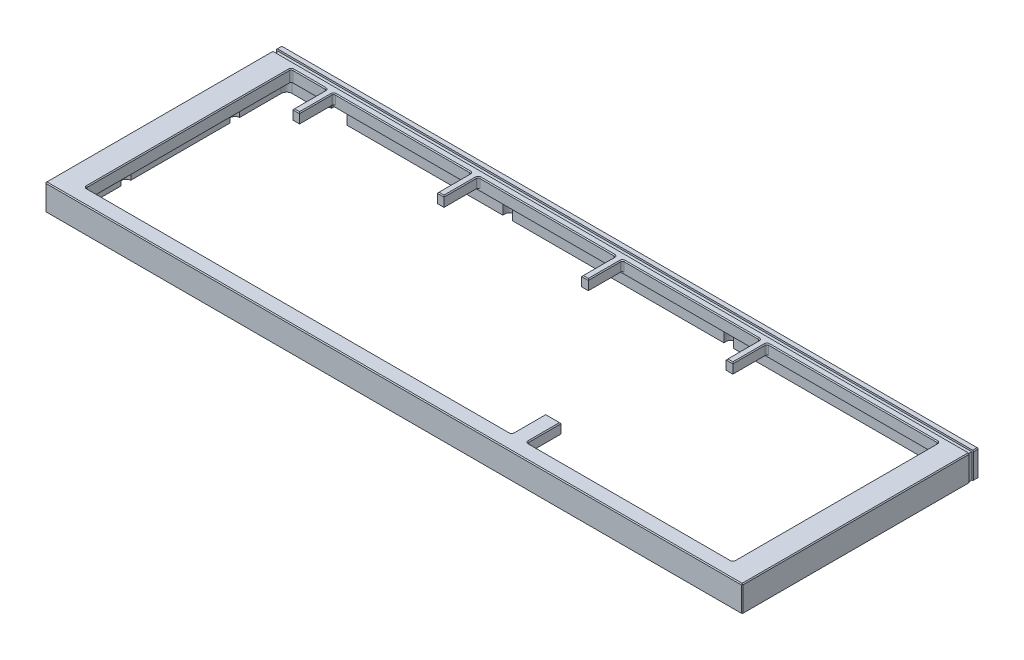
SolidWorks part; units mm, degrees
material "6061-T6 (SS)"
ref_plane "Front Plane" through (0, 0, 0) normal (0, 0, 1) x (1, 0, 0)
ref_plane "Top Plane" through (0, 0, 0) normal (0, 1, 0) x (1, 0, 0)
ref_plane "Right Plane" through (0, 0, 0) normal (1, 0, 0) x (0, 0, -1)
sketch "Sketch1" plane through (0, 0, 0) normal (0, 1, 0) x (1, 0, 0)
  line L1 (0, 0) -> (390.74, 0)
  line L2 (0, 0) -> (0, 132.7)
  line L3 (0, 132.7) -> (390.74, 132.7)
  line L4 (390.74, 0) -> (390.74, 132.7)
  line L5 (13.92, 124) -> (376.82, 124)
  line L6 (13.92, 124) -> (13.92, 8.7)
  line L7 (13.92, 8.7) -> (376.82, 8.7)
  line L8 (376.82, 124) -> (376.82, 8.7)
  point P9 (195.37, 124)
  point P10 (195.37, 132.7)
  point P11 (13.92, 66.35)
  point P12 (0, 66.35)
  dimension "D1" = 362.9
  dimension "D2" = 115.3
  dimension "D3" = 8.7
  dimension "D4" = 13.92
extrude "Main Body" add sketch "Sketch1" along normal blind 14.8
sketch "Sketch2" plane through (0, 0, 0) normal (0, -1, 0) x (1, 0, 0)
  line L0 (390.74, -132.7) -> (0, -132.7) construction
  line L1 (388.74, -130.7) -> (2, -130.7)
  line L2 (388.74, -130.7) -> (388.74, -2)
  line L3 (388.74, -2) -> (2, -2)
  line L4 (2, -130.7) -> (2, -2)
  line L5 (390.74, 0) -> (390.74, -132.7) construction
  point P4 (195.37, -130.7)
  point P7 (195.37, -132.7)
  point P8 (388.74, -66.35)
  point P11 (390.74, -66.35)
  dimension "D1" = 2
  dimension "D2" = 2
extrude "Alignment Guide" cut sketch "Sketch2" against normal blind 1 contours L2 L1 L4 L3
sketch "Sketch3" plane through (0, 14.8, 0) normal (0, 1, 0) x (1, 0, 0)
  line L0 (13.92, 8.7) -> (376.82, 8.7) construction
  line L1 (252.82, 27.8) -> (261.52, 27.8)
  line L2 (252.82, 27.8) -> (252.82, 8.7)
  line L3 (252.82, 8.7) -> (261.52, 8.7)
  line L4 (261.52, 27.8) -> (261.52, 8.7)
  line L5 (376.82, 8.7) -> (376.82, 124) construction
  line L6 (376.82, 124) -> (13.92, 124) construction
  line L7 (33.92, 124) -> (37.72, 124)
  line L8 (33.92, 124) -> (33.92, 104.9)
  line L9 (33.92, 104.9) -> (37.72, 104.9)
  line L10 (37.72, 124) -> (37.72, 104.9)
  line L11 (13.92, 124) -> (13.92, 8.7) construction
  line L12 (114.92, 124) -> (118.72, 124)
  line L13 (114.92, 124) -> (114.92, 104.9)
  line L14 (114.92, 104.9) -> (118.72, 104.9)
  line L15 (118.72, 124) -> (118.72, 104.9)
  line L16 (195.82, 124) -> (199.62, 124)
  line L17 (195.82, 124) -> (195.82, 104.9)
  line L18 (195.82, 104.9) -> (199.62, 104.9)
  line L19 (199.62, 124) -> (199.62, 104.9)
  line L20 (276.82, 124) -> (280.62, 124)
  line L21 (276.82, 124) -> (276.82, 104.9)
  line L22 (276.82, 104.9) -> (280.62, 104.9)
  line L23 (280.62, 124) -> (280.62, 104.9)
  point P8 (257.17, 8.7)
  dimension "D1" = 115.3
  dimension "D2" = 124
  dimension "D3" = 19.1
  dimension "D4" = 3.8
  dimension "D5" = 19.1
  dimension "D6" = 77.2
  dimension "D7" = 77.1
  dimension "D8" = 77.2
  dimension "D9" = 20
extrude "Blockers" add sketch "Sketch3" against normal blind 5.5
fillet "Fillet5" radius 1 14 edges at (280.62, 12.05, -124) (276.82, 12.05, -124) (195.82, 12.05, -124) (199.62, 12.05, -124) (118.72, 12.05, -124) (114.92, 12.05, -124) (33.92, 12.05, -124) (37.72, 12.05, -124) (13.92, 7.9, -124) (13.92, 7.9, -8.7) (252.82, 12.05, -8.7) (261.52, 12.05, -8.7) (376.82, 7.9, -8.7) (376.82, 7.9, -124)
sketch "Sketch4" plane through (0, 1, 0) normal (0, -1, 0) x (1, 0, 0)
  line L0 (0, 0) -> (390.74, 0) construction
  line L1 (381.27, -125.9) -> (9.47, -125.9)
  line L2 (381.27, -125.9) -> (381.27, -6.8)
  line L3 (381.27, -6.8) -> (9.47, -6.8)
  line L4 (9.47, -125.9) -> (9.47, -6.8)
  line L5 (390.74, 0) -> (390.74, -132.7) construction
  point P4 (195.37, -6.8)
  point P7 (195.37, 0)
  point P8 (381.27, -66.35)
  point P11 (390.74, -66.35)
  dimension "D1" = 119.1
  dimension "D2" = 371.8
extrude "PCB Cutout" cut sketch "Sketch4" against normal offset from surface (7.3 mm away) 6.5 up to face at (195.37, 14.8, -66.35)
fillet "Fillet4" radius 3 8 edges at (9.47, 4.65, -6.8) (9.47, 4.65, -125.9) (381.27, 4.65, -125.9) (381.27, 4.65, -6.8) (2, 0.5, -130.7) (2, 0.5, -2) (388.74, 0.5, -2) (388.74, 0.5, -130.7)
sketch "Sketch6" plane through (0, 1, 0) normal (0, -1, 0) x (1, 0, 0)
  line L0 (381.27, -9.8) -> (381.27, -122.9) construction
  line L1 (254.59, -127.1) -> (260.09, -127.1)
  line L2 (254.59, -127.1) -> (254.59, -125.9)
  line L3 (254.59, -125.9) -> (260.09, -125.9)
  line L4 (260.09, -127.1) -> (260.09, -125.9)
  line L5 (12.47, -125.9) -> (378.27, -125.9) construction
  line L11 (378.27, -6.8) -> (12.47, -6.8) construction
  line L16 (260.09, -6.8) -> (254.59, -6.8)
  line L17 (260.09, -6.8) -> (260.09, -4.8)
  line L18 (260.09, -4.8) -> (254.59, -4.8)
  line L19 (254.59, -6.8) -> (254.59, -4.8)
  line L21 (0, 0) -> (390.74, 0) construction
  line L24 (390.74, -66.35) -> (195.37, -66.35) construction
  line L25 (390.74, 0) -> (390.74, -132.7) construction
  line L26 (328.6755, -66.35) -> (328.6755, -130.7) construction
  line L27 (385.74, -130.7) -> (5, -130.7) construction
  line L28 (328.6755, -66.35) -> (328.6755, -8.7) construction
  line L29 (375.82, -8.7) -> (14.92, -8.7) construction
  line L55 (390.74, -132.7) -> (0, -132.7) construction
  line L56 (195.37, -132.7) -> (195.37, 0) construction
  line L57 (136.15, -6.8) -> (136.15, -4.8)
  line L58 (130.65, -4.8) -> (136.15, -4.8)
  line L59 (130.65, -6.8) -> (130.65, -4.8)
  line L60 (130.65, -6.8) -> (136.15, -6.8)
  line L61 (130.65, -127.1) -> (130.65, -125.9)
  line L62 (136.15, -125.9) -> (130.65, -125.9)
  line L63 (136.15, -127.1) -> (136.15, -125.9)
  line L64 (136.15, -127.1) -> (130.65, -127.1)
  circle A0 centre (381.07, -96.85) radius 2.75
  circle A1 centre (381.07, -35.85) radius 2.75
  circle A2 centre (257.34, -4.8) radius 2.75
  circle A3 centre (257.34, -127.1) radius 2.75
  circle A8 centre (133.4, -4.8) radius 2.75
  circle A9 centre (9.67, -35.85) radius 2.75
  circle A10 centre (9.67, -96.85) radius 2.75
  circle A11 centre (133.4, -127.1) radius 2.75
  point P25 (195.37, -66.35)
  point P32 (257.34, -125.9)
  point P33 (257.34, -6.8)
  line M17 (12.47, -6.8) -> (378.27, -6.8)
  line M18 (381.27, -9.8) -> (381.27, -122.9)
  line M19 (378.27, -125.9) -> (12.47, -125.9)
  line M20 (9.47, -122.9) -> (9.47, -9.8)
  dimension "D4" = 5.5
  dimension "D5" = 133.4
  dimension "D1" = 30.5
  dimension "D2" = 4.8
  dimension "D3" = 30.5
  dimension "D6" = 0.2
  dimension "D7" = 5.6
extrude "PlateTabs" cut sketch "Sketch6" against normal up to surface (7.3 mm away) contours A0 M18 | A1 M18 | A2 L19 M17 | L16 A2 L18 | A2 L17 M17 | L18 A2 | L1 A3 | L1 A3 L3 | A3 L2 M19 | A11 L64 | A11 L64 L62 | A10 M20 | A9 M20 | A8 L58 | A8 L60 L58 | A3 L4 M19 | A8 L59 M17 | L57 A8 M17 | A11 L63 M19 | L61 A11 M19
sketch "Sketch9" plane through (0, 0, -132.7) normal (0, 0, -1) x (-1, 0, 0)
  line L1 (-41.8, 0) -> (-29.8, 0)
  line L2 (-41.8, 0) -> (-41.8, 3.2)
  line L3 (-41.8, 3.2) -> (-29.8, 3.2)
  line L4 (-29.8, 0) -> (-29.8, 3.2)
  line L5 (-390.74, 0) -> (0, 0) construction
  line L7 (0, 14.8) -> (0, 0) construction
  point P6 (-35.8, 3.2)
  dimension "D1" = 3.2
  dimension "D3" = 12
  dimension "D4" = 35.8
extrude "USB Cutout" cut sketch "Sketch9" against normal up to surface (8.7 mm away) up to face at (164.89, 11.95, -124)
sketch "Sketch11" plane through (0, 0, -125.9) normal (0, 0, 1) x (1, 0, 0)
  line L0 (130.65, 8.3) -> (12.47, 8.3) construction
  line L1 (43.3, 1) -> (28.3, 1)
  line L2 (43.3, 1) -> (43.3, 8.3)
  line L3 (43.3, 8.3) -> (28.3, 8.3)
  line L4 (28.3, 1) -> (28.3, 8.3)
  line L7 (12.47, 1) -> (29.8, 1) construction
  line L8 (29.8, 3.2) -> (41.8, 3.2) construction
  point P8 (35.8, 1)
  point P18 (35.8, 3.2)
  dimension "D1" = 15
extrude "PCB Clearance" cut sketch "Sketch11" against normal blind 3.9
fillet "Fillet7" radius 2.5 2 edges at (28.3, 4.65, -129.8) (43.3, 4.65, -129.8)
sketch "Sketch12" plane through (0, 8.3, 0) normal (0, -1, 0) x (1, 0, 0)
  line L0 (195.37, -132.7) -> (195.37, 0) construction
  line L2 (14.92, -124) -> (375.82, -124) construction
  line L3 (0, 0) -> (390.74, 0) construction
  line L4 (390.74, 0) -> (390.74, -132.7) construction
  line L5 (390.74, -132.7) -> (41.8, -132.7) construction
  line L8 (376.82, -123) -> (376.82, -9.7) construction
  line L9 (375.82, -8.7) -> (14.92, -8.7) construction
  arc A0 (381.27, -38.5927) -> (381.27, -33.1073) centre (381.07, -35.85) ccw construction
  arc A1 (381.27, -99.5927) -> (381.27, -94.1073) centre (381.07, -96.85) ccw construction
  point P0 (257.34, -127.1)
  point P1 (381.42, -96.85)
  point P2 (381.42, -35.85)
  point P3 (257.34, -4.8)
  point P8 (133.4, -4.8)
  point P10 (9.32, -35.85)
  point P14 (9.32, -96.85)
  point P16 (133.4, -127.1)
  point P34 (383.82, -35.85)
  point P39 (383.82, -96.85)
  dimension "D1" = 3.1
  dimension "D2" = 3.9
  dimension "D3" = 4.6
  dimension "D4" = 133.4
sketch "Sketch14" plane through (0, 1, 0) normal (0, -1, 0) x (1, 0, 0)
  line L0 (195.37, -132.7) -> (195.37, 0) construction
  line L2 (0, 0) -> (390.74, 0) construction
  line L3 (390.74, -132.7) -> (41.8, -132.7) construction
  line L5 (195.37, -66.35) -> (390.74, -66.35) construction
  line L6 (390.74, 0) -> (390.74, -132.7) construction
  line L7 (388.74, -127.7) -> (388.74, -5) construction
  line L8 (385.74, -130.7) -> (41.8, -130.7) construction
  line L9 (385.74, -2) -> (5, -2) construction
  point P8 (385.04, -111.35)
  point P9 (385.04, -66.35)
  point P10 (385.04, -21.35)
  point P11 (280.74, -4.4)
  point P20 (280.74, -128.3)
  point P22 (110, -4.4)
  point P28 (110, -128.3)
  point P29 (5.7, -21.35)
  point P30 (5.7, -66.35)
  point P31 (5.7, -111.35)
  dimension "D1" = 2.4
  dimension "D2" = 2.4
  dimension "D3" = 110
  dimension "D4" = 45
  dimension "D5" = 45
  dimension "D6" = 3.7
chamfer "Chamfer1" distance 0.5 42 edges at (14.2129, 14.8, -8.9929) (133.37, 14.8, -8.7) (252.5271, 14.8, -8.9929) (252.82, 14.8, -18.75) (257.17, 14.8, -27.8) (261.52, 14.8, -18.75) (261.8129, 14.8, -8.9929) (319.17, 14.8, -8.7) (376.5271, 14.8, -8.9929) (376.82, 14.8, -66.35) (376.5271, 14.8, -123.7071) (328.72, 14.8, -124) (280.9129, 14.8, -123.7071) (280.62, 14.8, -113.95) (278.72, 14.8, -104.9) (276.82, 14.8, -113.95) (276.5271, 14.8, -123.7071) (238.22, 14.8, -124) (199.9129, 14.8, -123.7071) (199.62, 14.8, -113.95) (197.72, 14.8, -104.9) (195.82, 14.8, -113.95) (195.5271, 14.8, -123.7071) (157.27, 14.8, -124) (119.0129, 14.8, -123.7071) (118.72, 14.8, -113.95) (116.82, 14.8, -104.9) (114.92, 14.8, -113.95) (114.6271, 14.8, -123.7071) (76.32, 14.8, -124) (38.0129, 14.8, -123.7071) (37.72, 14.8, -113.95) (35.82, 14.8, -104.9) (33.92, 14.8, -113.95) (33.6271, 14.8, -123.7071) (23.92, 14.8, -124) (14.2129, 14.8, -123.7071) (13.92, 14.8, -66.35) (195.37, 14.8, -132.7) (390.74, 14.8, -66.35) (195.37, 14.8, 0) (0, 14.8, -66.35)
chamfer "Chamfer2" distance 0.5 9 edges at (0, 7.15, -132.7) (216.27, 0, -132.7) (14.9, 0, -132.7) (390.74, 7.15, -132.7) (390.74, 0, -66.35) (390.74, 7.15, 0) (0, 7.15, 0) (195.37, 0, 0) (0, 0, -66.35)
sketch "Sketch27" plane through (0, 14.8, 0) normal (0, 1, 0) x (1, 0, 0)
  line L0 (0, 0.5) -> (0, 132.2) construction
  line L1 (0, 129.7) -> (390.74, 129.7)
  line L2 (0, 129.7) -> (0, 127.2)
  line L3 (0, 127.2) -> (390.74, 127.2)
  line L4 (390.74, 129.7) -> (390.74, 127.2)
  line L5 (390.74, 132.2) -> (390.74, 0.5) construction
  line L8 (0.5, 132.7) -> (390.24, 132.7) construction
  dimension "D1" = 2.5
  dimension "D2" = 3
extrude "Cut-Extrude11" cut sketch "Sketch27" against normal blind 1
sketch "Sketch28" plane through (0, 13.8, 0) normal (0, 1, 0) x (1, 0, 0)
  line L1 (0, 129.7) -> (1, 129.7)
  line L2 (0, 129.7) -> (0, 127.2)
  line L3 (0, 127.2) -> (1, 127.2)
  line L4 (1, 129.7) -> (1, 127.2)
  line L5 (389.74, 129.7) -> (390.74, 129.7)
  line L6 (389.74, 129.7) -> (389.74, 127.2)
  line L7 (389.74, 127.2) -> (390.74, 127.2)
  line L8 (390.74, 129.7) -> (390.74, 127.2)
  line L9 (390.74, 129.7) -> (0, 129.7) construction
  line L10 (0, 127.2) -> (390.74, 127.2) construction
  dimension "D1" = 1
  dimension "D2" = 1
extrude "Cut-Extrude12" cut sketch "Sketch28" against normal through all
sketch "Sketch21" [suppressed] plane through (0, 14.8, 0) normal (0, 1, 0) x (1, 0, 0)
  line L0 (0.5, 132.7) -> (390.24, 132.7) construction
  line L1 (382.53, 132.7) -> (385.03, 132.7)
  line L2 (382.53, 132.7) -> (382.53, 72.7)
  line L3 (382.53, 72.7) -> (385.03, 72.7)
  line L4 (385.03, 132.7) -> (385.03, 72.7)
  line L5 (390.74, 132.2) -> (390.74, 129.7) construction
  line L6 (390.74, 129.1) -> (294.74, 129.1)
  line L7 (390.74, 129.1) -> (390.74, 127.6)
  line L8 (390.74, 127.6) -> (294.74, 127.6)
  line L9 (294.74, 129.1) -> (294.74, 127.6)
  line L10 (362.9081, 132.2) -> (362.9081, 124.5) construction
  line L11 (390.24, 132.2) -> (0.5, 132.2) construction
  line L12 (281.62, 124.5) -> (375.82, 124.5) construction
  line L13 (365.5702, 129.1) -> (365.5702, 127.6) construction
  line L14 (377.32, 119.5259) -> (390.24, 119.5259) construction
  line L15 (377.32, 123) -> (377.32, 9.7) construction
  line L16 (390.24, 0.5) -> (390.24, 127.2) construction
  line L17 (382.53, 116.0504) -> (385.03, 116.0504) construction
  point P28 (383.78, 116.0504)
  point P29 (383.78, 119.5259)
  point P30 (365.5702, 128.35)
  point P31 (362.9081, 128.35)
  dimension "D1" = 2.5
  dimension "D2" = 1.5
  dimension "D3" = 60
  dimension "D4" = 96
extrude "Cut-Extrude5" [suppressed] cut sketch "Sketch21" against normal blind 1
sketch "Sketch23" [suppressed] plane through (390.74, 0, 0) normal (1, 0, 0) x (0, 0, -1)
  line L0 (129.1, 13.8) -> (129.1, 14.3) construction
  line L1 (127.6, 13.8) -> (129.1, 13.8)
  line L2 (127.6, 13.8) -> (127.6, 0)
  line L3 (127.6, 0) -> (129.1, 0)
  line L4 (129.1, 13.8) -> (129.1, 0)
extrude "Cut-Extrude6" [suppressed] cut sketch "Sketch23" against normal blind 1
sketch "Sketch20" plane through (0, 14.8, 0) normal (0, 1, 0) x (1, 0, 0)
  line L0 (0, 0.5) -> (0, 127.2) construction
  line L1 (0, 129.1) -> (390.74, 129.1)
  line L2 (0, 129.1) -> (0, 127.6)
  line L3 (0, 127.6) -> (390.74, 127.6)
  line L4 (390.74, 129.1) -> (390.74, 127.6)
  line L5 (390.74, 132.2) -> (390.74, 129.7) construction
  line L6 (0.5, 132.7) -> (390.24, 132.7) construction
  line L7 (381.7523, 132.7) -> (384.2523, 132.7)
  line L8 (381.7523, 132.7) -> (381.7523, 0)
  line L9 (381.7523, 0) -> (384.2523, 0)
  line L10 (384.2523, 132.7) -> (384.2523, 0)
  line L11 (390.24, 0) -> (0.5, 0) construction
  line L12 (376.82, 111.1489) -> (390.74, 111.1489) construction
  line L13 (376.82, 9.7) -> (376.82, 123) construction
  line L14 (381.7523, 114.604) -> (384.2523, 114.604) construction
  line L15 (369.2566, 124.5) -> (369.2566, 132.2) construction
  line L16 (281.62, 124.5) -> (375.82, 124.5) construction
  line L17 (390.24, 132.2) -> (0.5, 132.2) construction
  line L18 (371.0168, 127.6) -> (371.0168, 129.1) construction
  point P30 (371.0168, 128.35)
  point P31 (369.2566, 128.35)
  dimension "D1" = 2.5
  dimension "D2" = 1.5
extrude "Cut-Extrude4" [suppressed] cut sketch "Sketch20" against normal blind 1
sketch "Sketch19" plane through (0, 14.8, 0) normal (0, 1, 0) x (1, 0, 0)
  line L0 (0.5, 132.7) -> (390.24, 132.7) construction
  line L1 (5.46, 132.7) -> (8.46, 132.7)
  line L2 (5.46, 132.7) -> (5.46, 0)
  line L3 (5.46, 0) -> (8.46, 0)
  line L4 (8.46, 132.7) -> (8.46, 0)
  line L7 (382.28, 132.7) -> (385.28, 132.7)
  line L8 (382.28, 132.7) -> (382.28, 0)
  line L9 (382.28, 0) -> (385.28, 0)
  line L10 (385.28, 132.7) -> (385.28, 0)
  line L11 (390.24, 0) -> (0.5, 0) construction
  line L12 (377.32, 110.209) -> (390.24, 110.209) construction
  line L13 (377.32, 123) -> (377.32, 9.7) construction
  line L14 (390.24, 0.5) -> (390.24, 127.2) construction
  line L15 (382.28, 106.8719) -> (385.28, 106.8719) construction
  line L16 (0.5, 106.8719) -> (13.42, 106.8719) construction
  line L17 (0.5, 132.2) -> (0.5, 129.7) construction
  line L18 (13.42, 9.7) -> (13.42, 123) construction
  line L19 (5.46, 102.7297) -> (8.46, 102.7297) construction
  point P12 (383.78, 106.8719)
  point P14 (383.78, 110.209)
  point P30 (6.96, 102.7297)
  point P31 (6.96, 106.8719)
  dimension "D1" = 3
  dimension "D2" = 3
extrude "Cut-Extrude3" [suppressed] cut sketch "Sketch19" against normal blind 1
sketch "Sketch17" plane through (0, 14.8, 0) normal (0, 1, 0) x (1, 0, 0)
  line L0 (390.24, 0.5) -> (390.24, 127.2) construction
  line L1 (5.71, 129.6) -> (385.03, 129.6)
  line L2 (5.71, 129.6) -> (5.71, -1.9)
  line L3 (5.71, -1.9) -> (385.03, -1.9)
  line L4 (385.03, 129.6) -> (385.03, -1.9)
  line L5 (8.21, 127.1) -> (382.53, 127.1)
  line L6 (8.21, 127.1) -> (8.21, 0.6)
  line L7 (8.21, 0.6) -> (382.53, 0.6)
  line L8 (382.53, 127.1) -> (382.53, 0.6)
  line L9 (390.24, 132.2) -> (0.5, 132.2) construction
  line L10 (21.2533, 132.2) -> (21.2533, 124.5) construction
  line L11 (14.92, 124.5) -> (32.92, 124.5) construction
  line L12 (25.2757, 129.6) -> (25.2757, 127.1) construction
  line L13 (0.5, 116.1326) -> (13.42, 116.1326) construction
  line L14 (0.5, 132.2) -> (0.5, 129.7) construction
  line L15 (13.42, 9.7) -> (13.42, 123) construction
  line L16 (5.71, 120.1548) -> (8.21, 120.1548) construction
  point P8 (382.53, 63.85)
  point P9 (385.03, 63.85)
  point P12 (390.24, 63.85)
  point P13 (195.37, 129.6)
  point P14 (195.37, 127.1)
  point P17 (195.37, 132.2)
  point P24 (25.2757, 128.35)
  point P25 (21.2533, 128.35)
  point P34 (6.96, 116.1326)
  point P35 (6.96, 120.1548)
  dimension "D1" = 2.5
  dimension "D2" = 2.5
extrude "Cut-Extrude1" [suppressed] cut sketch "Sketch17" against normal blind 1
hole_wizard "M3x0.5 Tapped Hole1" positions "3DSketch1" profile "Sketch29" tap size "M3x0.5" standard "ANSI Metric"
sketch3d "3DSketch1"
  point P0 (385.04, 1, -111.35)
  point P3 (385.04, 1, -21.35)
  point P6 (280.74, 1, -4.4)
  point P9 (110, 1, -4.4)
  point P12 (5.7, 1, -21.35)
  point P15 (5.7, 1, -66.35)
  point P18 (5.7, 1, -111.35)
  point P21 (110, 1, -128.3)
  point P24 (280.74, 1, -128.3)
  point P28 (385.04, 1, -66.35)
sketch "Sketch29" plane through (385.04, 1, -111.35) normal (1, 0, 0) x (0, 0, -1)
  line L0 (0, 0) -> (0, 4.7511)
  line L1 (0, 4.7511) -> (1.25, 4)
  line L2 (1.25, 4) -> (1.25, 0)
  line L5 (1.25, 0) -> (0, 0)
  line L10 (0, 4.7511) -> (-1.25, 4) construction
  line L11 (0, -6.35) -> (0, 107.95) construction
  dimension "Tap Drill Dia." = 2.5
  dimension "Tap Drill Depth" = 4
  dimension "Drill Angle" = 118
cosmetic thread "Hole Thread1" parameters "D1"=4, "D2"=3
cosmetic thread "Hole Thread2" parameters "D1"=4, "D2"=3
cosmetic thread "Hole Thread3" parameters "D1"=4, "D2"=3
cosmetic thread "Hole Thread4" parameters "D1"=4, "D2"=3
cosmetic thread "Hole Thread5" parameters "D1"=4, "D2"=3
cosmetic thread "Hole Thread6" parameters "D1"=4, "D2"=3
cosmetic thread "Hole Thread7" parameters "D1"=4, "D2"=3
cosmetic thread "Hole Thread8" parameters "D1"=4, "D2"=3
cosmetic thread "Hole Thread9" parameters "D1"=4, "D2"=3
cosmetic thread "Hole Thread18" parameters "D1"=4, "D2"=3
hole_wizard "M2x0.4 Tapped Hole1" positions "3DSketch3" profile "Sketch31" tap size "M2x0.4" standard "ANSI Metric"
sketch3d "3DSketch3"
  point P0 (381.42, 8.3, -96.85)
  point P3 (381.42, 8.3, -35.85)
  point P7 (257.34, 8.3, -4.8)
  point P10 (133.4, 8.3, -4.8)
  point P13 (9.32, 8.3, -35.85)
  point P16 (9.32, 8.3, -96.85)
  point P19 (133.4, 8.3, -127.1)
  point P22 (257.34, 8.3, -127.1)
sketch "Sketch31" plane through (381.42, 8.3, -96.85) normal (1, 0, 0) x (0, 0, -1)
  line L0 (0, 0) -> (0, 4.4807)
  line L1 (0, 4.4807) -> (0.8, 4)
  line L2 (0.8, 4) -> (0.8, 0)
  line L5 (0.8, 0) -> (0, 0)
  line L10 (0, 4.4807) -> (-0.8, 4) construction
  line L11 (0, -6.35) -> (0, 107.95) construction
  dimension "Tap Drill Dia." = 1.6
  dimension "Tap Drill Depth" = 4
  dimension "Drill Angle" = 118
cosmetic thread "Hole Thread19" parameters "D1"=4, "D2"=2
cosmetic thread "Hole Thread20" parameters "D1"=4, "D2"=2
cosmetic thread "Hole Thread21" parameters "D1"=4, "D2"=2
cosmetic thread "Hole Thread22" parameters "D1"=4, "D2"=2
cosmetic thread "Hole Thread23" parameters "D1"=4, "D2"=2
cosmetic thread "Hole Thread24" parameters "D1"=4, "D2"=2
cosmetic thread "Hole Thread25" parameters "D1"=4, "D2"=2
cosmetic thread "Hole Thread26" parameters "D1"=4, "D2"=2
fillet "Fillet8" radius 0.1 9 edges at (213.77, 0, -130.7) (387.8613, 0, -129.8213) (17.4, 0, -130.7) (2.8787, 0, -129.8213) (2, 0, -66.35) (2.8787, 0, -2.8787) (195.37, 0, -2) (387.8613, 0, -2.8787) (388.74, 0, -66.35)
